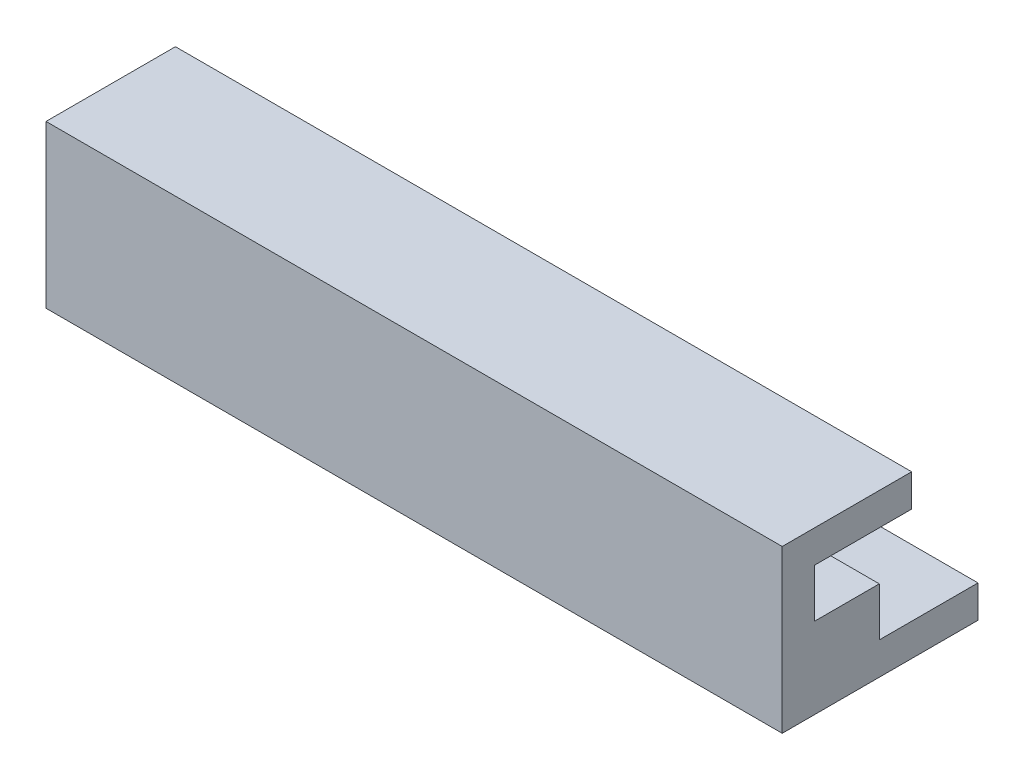
SolidWorks part; units mm, degrees
ref_plane "Alzado" through (0, 0, 0) normal (0, 0, 1) x (1, 0, 0)
ref_plane "Planta" through (0, 0, 0) normal (0, 1, 0) x (1, 0, 0)
ref_plane "Vista lateral" through (0, 0, 0) normal (1, 0, 0) x (0, 0, -1)
sketch "Croquis1" plane through (0, 0, 0) normal (0, 0, 1) x (1, 0, 0)
  line L0 (-48.9396, 26.5035) -> (-8.4396, 26.5035)
  line L1 (-49.9396, 5.5035) -> (-49.9396, 1.5035)
  line L2 (-48.9396, 26.5035) -> (-49.9396, 26.5035)
  line L6 (-8.4396, 26.5035) -> (-4.4396, 26.5035)
  line L7 (-49.9396, 26.5035) -> (-49.9396, 5.5035)
  line L8 (-4.4396, 26.5035) -> (-4.4396, 1.5035)
  line L9 (-8.4396, 1.5035) -> (-49.9396, 1.5035)
  line L10 (-4.4396, 1.5035) -> (-8.4396, 1.5035)
extrude "Saliente-Extruir1" add sketch "Croquis1" along normal blind 2
sketch "Croquis3" plane through (0, 0, 0) normal (0, 0, 1) x (1, 0, 0)
  line L0 (-48.9396, 26.5035) -> (-8.4396, 26.5035)
  line L1 (-49.9396, 26.5035) -> (-49.9396, 1.5035)
  line L2 (-10.4396, 3.5035) -> (-47.9396, 3.5035)
  line L3 (-8.4396, 26.5035) -> (-4.4396, 26.5035)
  line L5 (-4.4396, 26.5035) -> (-4.4396, 1.5035)
  line L6 (-10.4396, 24.5035) -> (-6.4396, 24.5035)
  line L7 (-6.4396, 24.5035) -> (-6.4396, 3.5035)
  line L8 (-6.4396, 3.5035) -> (-10.4396, 3.5035)
  line L9 (-49.9396, 1.5035) -> (-4.4396, 1.5035) construction
  line L10 (-4.4396, 1.5035) -> (-49.9396, 1.5035)
  line L12 (-47.9396, 3.5035) -> (-47.9396, 5.5035)
  line L16 (-49.9396, 26.5035) -> (-48.9396, 26.5035)
  line L21 (-47.9396, 5.5035) -> (-47.9396, 24.5035)
  line L22 (-47.9396, 24.5035) -> (-47.9396, 24.5035)
  line L23 (-47.9396, 24.5035) -> (-10.4396, 24.5035)
  line L27 (-49.9396, 5.5035) -> (-49.9396, 26.5035) construction
  line L28 (-49.9396, 1.5035) -> (-49.9396, 5.5035) construction
  line L29 (-8.4396, 6.5035) -> (-8.4396, 26.5035) construction
  line L30 (-8.4396, 5.5035) -> (-8.4396, 1.5035) construction
  line L31 (-8.4396, 6.5035) -> (-8.4396, 5.5035) construction
  line L32 (-10.4396, 6.5035) -> (-10.4396, 24.5035) construction
  line L33 (-10.4396, 6.5035) -> (-10.4396, 5.5035) construction
  line L34 (-10.4396, 5.5035) -> (-10.4396, 3.5035) construction
  line L36 (-8.4396, 1.5035) -> (-49.9396, 1.5035) construction
extrude "Saliente-Extruir2" add sketch "Croquis3" along normal blind 24
sketch "Croquis4" plane through (0, 0, 0) normal (1, 0, 0) x (0, 0, -1)
  line L0 (-2, 5.4077) -> (-28.8385, 5.4077)
  line L2 (-28.8385, 5.4077) -> (-28.8385, 22.4485)
  line L3 (-2, 22.4485) -> (-28.8385, 22.4485)
  line L4 (-2, 5.4077) -> (-2, 22.4485)
extrude "Cortar-Extruir1" cut sketch "Croquis4" against normal blind 70.1
ref_plane "Plano1" through (0, 26.5035, 0) normal (0, 1, 0) x (1, 0, 0)
sketch "Croquis5" plane through (0, 26.5035, 0) normal (0, 1, 0) x (1, 0, 0)
  line L0 (-49.9396, -20.6072) -> (-4.4396, -20.6072)
  line L2 (-49.9396, -24) -> (-49.9396, 0) construction
  line L3 (-49.9396, -20.6072) -> (-49.9396, -36.1)
  line L4 (-4.4396, -24) -> (-4.4396, 0) construction
  line L5 (-48.9396, -36.1) -> (-8.4396, -36.1)
  line L6 (-4.4396, -20.6072) -> (-4.4396, -36.1)
  line L7 (-4.4396, -36.1) -> (-8.4396, -36.1)
  line L12 (-49.9396, -36.1) -> (-48.9396, -36.1)
extrude "Saliente-Extruir3" add sketch "Croquis5" against normal blind 2
ref_plane "Plano2" through (0, 0, 36.1) normal (0, 0, 1) x (1, 0, 0)
sketch "Croquis6" plane through (0, 0, 36.1) normal (0, 0, 1) x (1, 0, 0)
  line L0 (-4.4396, 24.5035) -> (-49.9396, 24.5035)
  line L1 (-49.9396, 24.5035) -> (-49.9396, 33.5035)
  line L2 (-4.4396, 24.5035) -> (-4.4396, 33.5035)
  line L3 (-49.9396, 33.5035) -> (-49.9396, 34.5035)
  line L5 (-49.9396, 34.5035) -> (-4.4396, 34.5035)
  line L8 (-4.4396, 34.5035) -> (-4.4396, 33.5035)
extrude "Saliente-Extruir4" add sketch "Croquis6" against normal blind 2
sketch "Croquis7" plane through (0, 0, 36.1) normal (0, 0, 1) x (1, 0, 0)
  line L0 (-4.4396, 34.5035) -> (-49.9396, 34.5035)
  line L1 (-4.4396, 34.5035) -> (-4.4396, 32.5035)
  line L2 (-4.4396, 32.5035) -> (-49.9396, 32.5035)
  line L6 (-49.9396, 32.5035) -> (-49.9396, 34.5035)
extrude "Saliente-Extruir5" add sketch "Croquis7" against normal blind 8
sketch "Croquis8" plane through (0, 0, 36.1) normal (0, 0, 1) x (1, 0, 0)
  line L0 (-49.9396, 29.5035) -> (-49.9396, 26.5035)
  line L1 (-8.4396, 29.5035) -> (-4.4396, 29.5035)
  line L2 (-49.715, 29.5035) -> (-8.4396, 29.5035)
  line L3 (-49.9396, 24.5035) -> (-49.9396, 34.5035) construction
  line L5 (-8.4396, 26.5035) -> (-49.715, 26.5035)
  line L6 (-4.4396, 24.5035) -> (-4.4396, 34.5035) construction
  line L7 (18.755, 26.5035) -> (-18.755, 26.5035) construction
  line L8 (-49.9396, 26.5035) -> (-49.715, 26.5035)
  line L9 (-49.715, 29.5035) -> (-49.9396, 29.5035)
  line L10 (-4.4396, 29.5035) -> (-4.4396, 26.5035)
  line L11 (-4.4396, 26.5035) -> (-8.4396, 26.5035)
extrude "Saliente-Extruir6" add sketch "Croquis8" against normal blind 6
ref_plane "Plano4" through (0, 0, 24) normal (0, 0, 1) x (1, 0, 0)
sketch "Croquis9" plane through (0, 0, 24) normal (0, 0, 1) x (1, 0, 0)
  line L1 (13.0935, 53.3426) -> (-63.8689, 53.3426)
  line L2 (13.0935, 53.3426) -> (13.0935, -5.6152)
  line L3 (13.0935, -5.6152) -> (-63.8689, -5.6152)
  line L4 (-63.8689, 53.3426) -> (-63.8689, -5.6152)
extrude "Cortar-Extruir2" cut sketch "Croquis9" against normal blind 39
